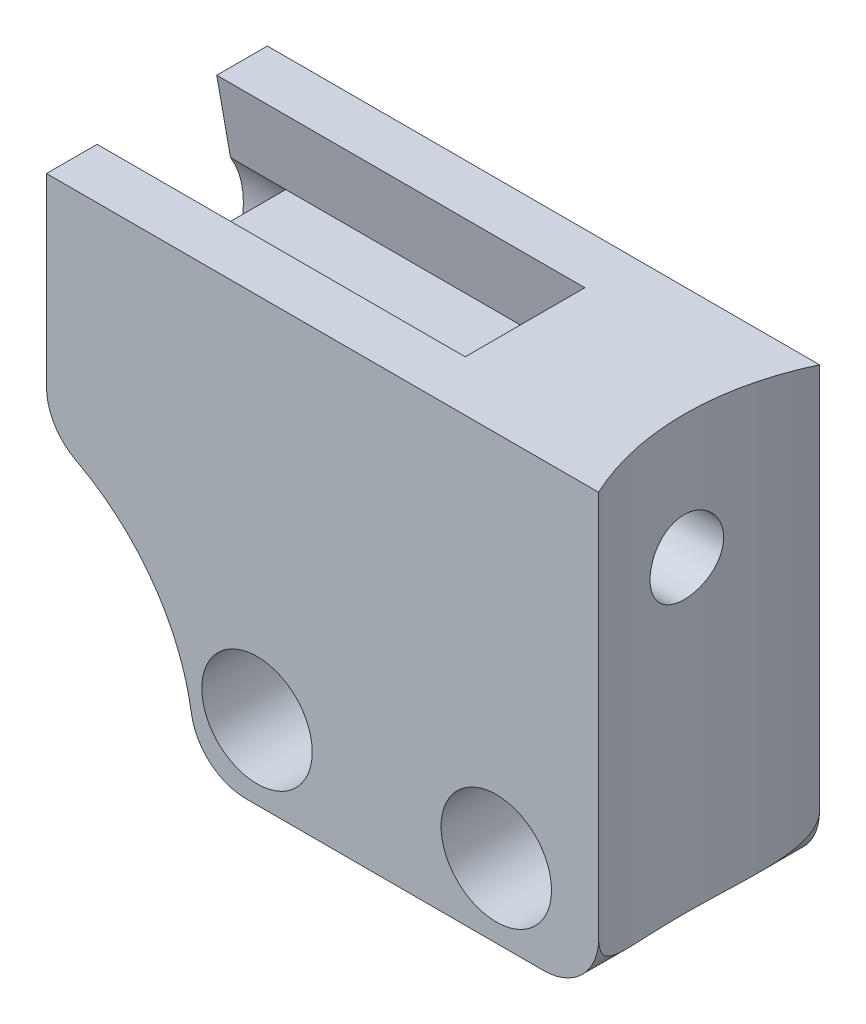
SolidWorks part; units mm, degrees
ref_plane "前视基准面" through (0, 0, 0) normal (0, 0, 1) x (1, 0, 0)
ref_plane "上视基准面" through (0, 0, 0) normal (0, 1, 0) x (1, 0, 0)
ref_plane "右视基准面" through (0, 0, 0) normal (1, 0, 0) x (0, 0, -1)
sketch "草图1" plane through (0, 0, 0) normal (0, 0, 1) x (1, 0, 0)
  line L1 (-15, 12) -> (15, 12)
  line L2 (-15, 12) -> (-15, 1.9561)
  line L3 (-4.1613, -12) -> (12, -12)
  line L4 (15, 12) -> (15, -9)
  line L5 (-15, 12) -> (15, -12) construction
  line L6 (-8.0265, -6.4212) -> (15, 12) construction
  arc A0 (-13.3961, -0.6992) -> (-7.1252, -9.4641) centre (-18.9807, -11.3205) cw
  circle A1 centre (-3.5619, -8) radius 3
  circle A2 centre (9.4381, -8) radius 3
  arc A3 (12, -12) -> (15, -9) centre (12, -9) ccw
  arc A4 (-4.1613, -12) -> (-7.1252, -9.4641) centre (-4.1613, -9) cw
  arc A5 (-13.3961, -0.6992) -> (-15, 1.9561) centre (-12, 1.9561) cw
  point P0 (0, 0)
  point P13 (0, 0)
  point P16 (15, -7.5753)
  point P17 (15, -8.2776)
  dimension "D3" = 12
  dimension "D4" = 6
  dimension "D8" = 3
  dimension "D1" = 30
  dimension "D2" = 24
  dimension "D5" = 13
  dimension "D6" = 4
  dimension "D7" = 5.5619
extrude "凸台-拉伸1" add sketch "草图1" along normal mid plane 12
sketch "草图2" plane through (-15, 0, 0) normal (-1, 0, 0) x (0, 0, 1)
  line L0 (0, 0) -> (0, 12.2476) construction
  line L2 (-3.25, 12) -> (3.25, 12)
  line L3 (6, 12) -> (-6, 12) construction
  line L4 (3.25, 12) -> (4, 7.7465)
  line L5 (4, 7.7465) -> (-4, 7.7465)
  line L6 (-4, 7.7465) -> (-3.25, 12)
  arc A2 (-4, 7.7465) -> (4, 7.7465) centre (0, 5.2787) ccw
  circle A3 centre (0, 5.2787) radius 2
  line M7 (6, 12) -> (-6, 12)
  dimension "D2" = 4
  dimension "D1" = 4.7
  dimension "D4" = 6.5
  dimension "D5" = 80
  dimension "D6" = 8
extrude "切除-拉伸3" cut sketch "草图2" against normal blind 20 contours L5 L0 L2 L6 | L0 L5 L4 M7
sketch "草图5" plane through (-15, 0, 0) normal (-1, 0, 0) x (0, 0, 1)
  line L0 (-4, 7.7465) -> (4, 7.7465)
  arc A0 (-4, 7.7465) -> (4, 7.7465) centre (0, 5.2787) ccw
  dimension "D1" = 4.7
extrude "切除-拉伸4" cut sketch "草图5" against normal blind 3
sketch "草图6" plane through (-12, 0, 0) normal (-1, 0, 0) x (0, 0, 1)
  circle A0 centre (0, 5.2787) radius 2
  dimension "D1" = 4
extrude "切除-拉伸5" cut sketch "草图6" against normal through all
sketch "草图7" plane through (0, 12, 0) normal (0, 1, 0) x (1, 0, 0)
  line L0 (15, -6) -> (-15, -6) construction
  line L1 (15, -6) -> (15, 6) construction
  line L2 (15, 6) -> (15, -6)
  arc A0 (15, 6) -> (15, -6) centre (27.6491, 0) ccw
  dimension "D1" = 14
extrude "切除-拉伸6" cut sketch "草图7" against normal through all
